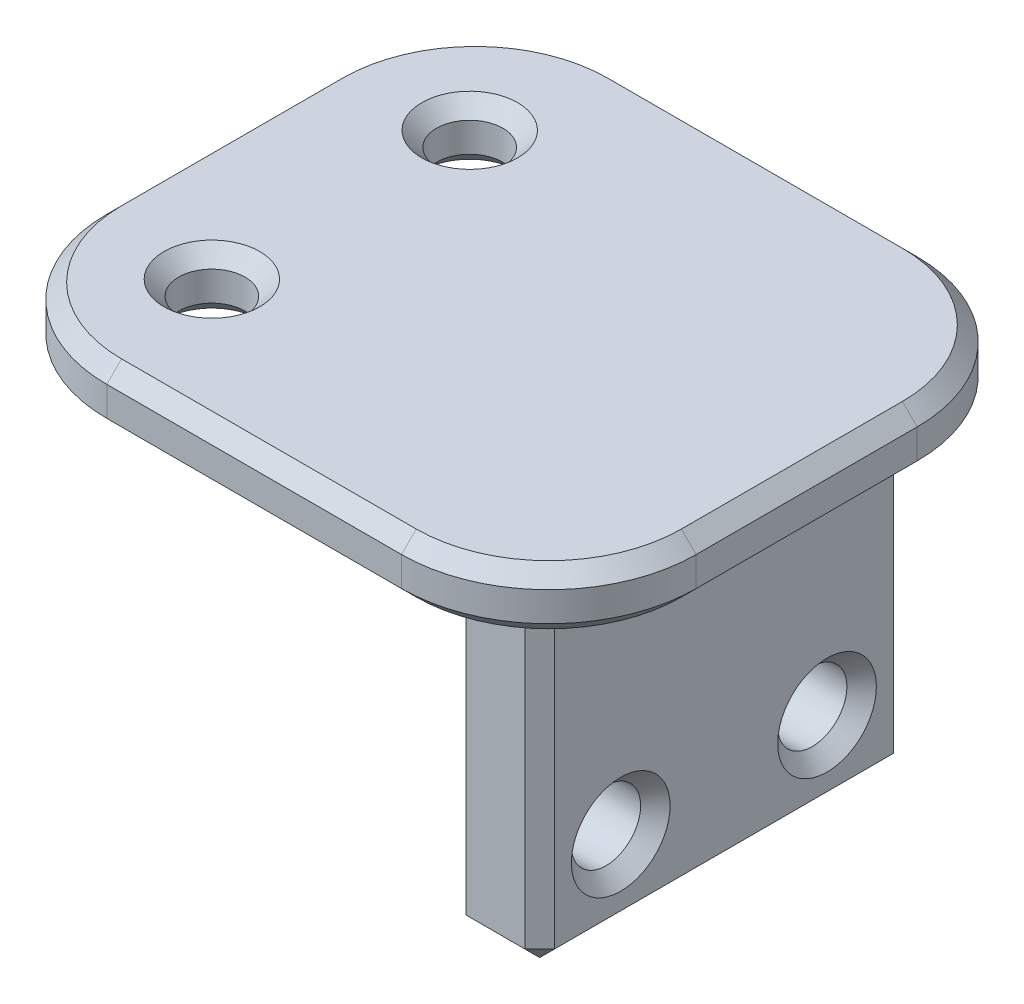
SolidWorks part; units mm, degrees
ref_plane "Front Plane" through (0, 0, 0) normal (0, 0, 1) x (1, 0, 0)
ref_plane "Top Plane" through (0, 0, 0) normal (0, 1, 0) x (1, 0, 0)
ref_plane "Right Plane" through (0, 0, 0) normal (1, 0, 0) x (0, 0, -1)
sketch "Sketch1" plane through (0, 0, 0) normal (0, 1, 0) x (1, 0, 0)
  line L0 (19.5019, 16.6283) -> (-20.4981, 16.6283)
  line L1 (19.5019, 16.6283) -> (19.5019, -18.3717)
  line L2 (19.5019, -18.3717) -> (-20.4981, -18.3717)
  line L3 (7.8819, -13.3717) -> (13.8819, -13.3717)
  line L4 (7.8819, 11.6283) -> (7.8819, -13.3717)
  line L5 (13.8819, 11.6283) -> (7.8819, 11.6283)
  line L6 (13.8819, -13.3717) -> (13.8819, 11.6283)
  line L7 (-20.4981, 16.6283) -> (-20.4981, -18.3717)
  line L8 (19.5019, 16.6283) -> (-20.4981, -18.3717) construction
  line L9 (19.5019, -18.3717) -> (-20.4981, 16.6283) construction
  circle A0 centre (-12.1181, -9.6217) radius 2.25
  circle A1 centre (-12.1181, 7.8783) radius 2.25
  point P12 (-0.4981, -0.8717)
  dimension "D1" = 40
extrude "Boss-Extrude1" add sketch "Sketch1" along normal blind 4
sketch "Sketch2" plane through (0, 4, 0) normal (0, 1, 0) x (1, 0, 0)
  line L4 (13.8819, -13.3717) -> (13.8819, 11.6283)
  line L5 (7.8819, -13.3717) -> (13.8819, -13.3717)
  line L6 (7.8819, 11.6283) -> (7.8819, -13.3717)
  line L7 (13.8819, 11.6283) -> (7.8819, 11.6283)
  line L8 (13.8819, -13.3717) -> (13.8819, 11.6283)
  line L9 (7.8819, -13.3717) -> (13.8819, -13.3717)
  line L10 (7.8819, 11.6283) -> (7.8819, -13.3717)
  line L11 (13.8819, 11.6283) -> (7.8819, 11.6283)
  dimension "D1" = 0
extrude "Boss-Extrude2" add sketch "Sketch2" against normal blind 26
sketch "Sketch3" plane through (13.8819, 0, 0) normal (1, 0, 0) x (0, 0, -1)
  line L0 (-0.8717, 0) -> (-0.8717, -22) construction
  line L1 (-13.3717, 0) -> (11.6283, 0) construction
  line L2 (-13.3717, -22) -> (11.6283, -22) construction
  circle A0 centre (6.1283, -16.5) radius 2.35
  circle A1 centre (-7.8717, -16.5) radius 2.35
  dimension "D3" = 4.7
  dimension "D1" = 7
  dimension "D2" = 5.5
extrude "Cut-Extrude1" cut sketch "Sketch3" against normal through all
fillet "Fillet1" radius 10 4 edges at (19.5019, 2, 18.3717) (19.5019, 2, -16.6283) (-20.4981, 2, -16.6283) (-20.4981, 2, 18.3717)
chamfer "Chamfer1" distance 1 angle 45 32 edges at (-12.1181, 4, -5.6283) (-12.1181, 4, 11.8717) (-17.5692, 4, 15.4428) (-20.4981, 4, 0.8717) (-17.5692, 4, -13.6993) (-0.4981, 4, -16.6283) (16.5729, 4, -13.6993) (19.5019, 4, 0.8717) (16.5729, 4, 15.4428) (-0.4981, 4, 18.3717) (7.8819, -16.5, 10.2217) (7.8819, -16.5, -3.7783) (13.8819, -16.5, 10.2217) (13.8819, -16.5, -8.4783) (7.8819, -22, 0.8717) (7.8819, -11, 13.3717) (10.8819, -22, 13.3717) (7.8819, -11, -11.6283) (10.8819, -22, -11.6283) (13.8819, -11, -11.6283) (13.8819, -22, 0.8717) (13.8819, -11, 13.3717) (-0.4981, 0, -16.6283) (-17.5692, 0, -13.6993) (16.5729, 0, -13.6993) (-20.4981, 0, 0.8717) (19.5019, 0, 0.8717) (-17.5692, 0, 15.4428) (16.5729, 0, 15.4428) (-0.4981, 0, 18.3717) (-12.1181, 0, -5.6283) (-12.1181, 0, 11.8717)
